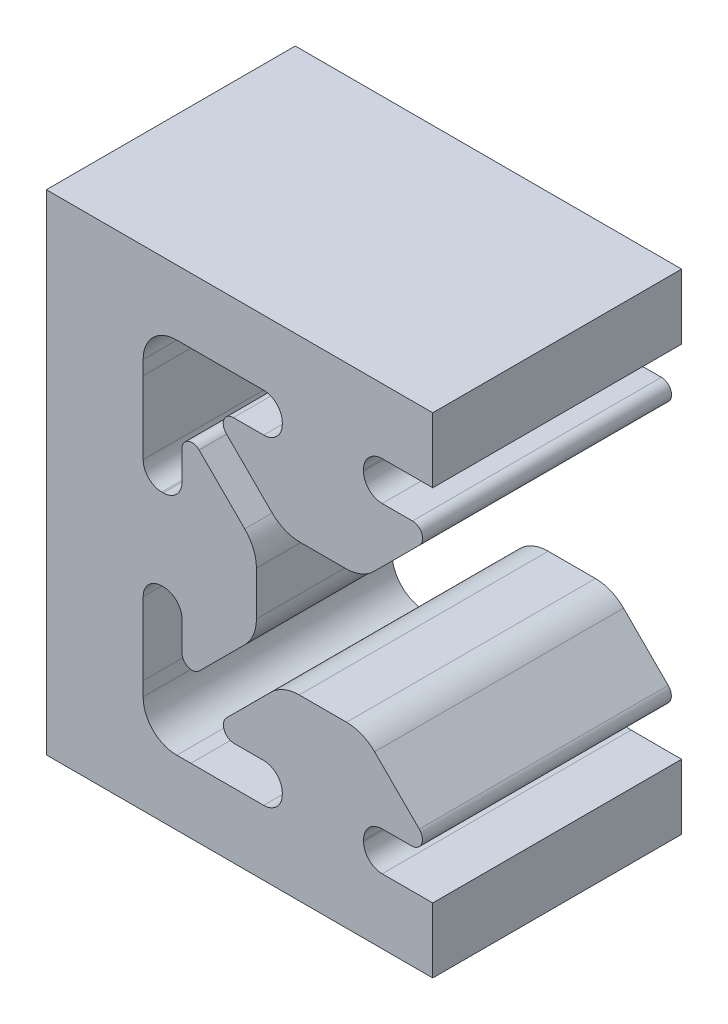
SolidWorks part; units mm, degrees
ref_plane "Front Plane" through (0, 0, 0) normal (0, 0, 1) x (1, 0, 0)
ref_plane "Top Plane" through (0, 0, 0) normal (0, 1, 0) x (1, 0, 0)
ref_plane "Right Plane" through (0, 0, 0) normal (1, 0, 0) x (0, 0, -1)
sketch "Sketch1" plane through (0, 0, 0) normal (0, 0, 1) x (1, 0, 0)
  line L0 (6.3331, -12.7) -> (5.3171, -12.7) construction
  line L1 (-5.3171, -12.7) -> (-6.3331, -12.7) construction
  line L2 (-9.5504, -12.7) -> (-10.5664, -12.6998) construction
  line L3 (-12.6998, -10.5664) -> (-12.7, -9.5504) construction
  line L4 (-12.7, -6.3331) -> (-12.7, -5.3171) construction
  line L5 (-12.7, 5.3171) -> (-12.7, 6.4021) construction
  line L6 (-12.7, 9.5504) -> (-12.6998, 10.5664) construction
  line L7 (-10.5664, 12.6998) -> (-9.5504, 12.7) construction
  line L8 (-6.3331, 12.7) -> (-5.3171, 12.7) construction
  line L9 (5.3171, 12.7) -> (6.3331, 12.7) construction
  line L10 (7.9418, -13) -> (7.9418, -17.7)
  line L12 (7.9418, -17.7) -> (-20, -17.7)
  line L13 (-20, -17.7) -> (-20, 17.6998)
  line L15 (-20, 17.6998) -> (7.9418, 17.6998)
  line L16 (7.9418, 17.6998) -> (7.9418, 13)
  line L17 (7.9418, 13) -> (6.3331, 13)
  line L18 (5.3171, 13) -> (6.3331, 13)
  line L19 (5.3171, 13) -> (4.2875, 13)
  line L20 (2.9385, 11.651) -> (2.9385, 11.5392)
  line L21 (4.2875, 10.1902) -> (6.4768, 10.1902)
  line L22 (6.9951, 8.9367) -> (3.6864, 5.6355)
  line L23 (1.6558, 4.7958) -> (-1.6558, 4.7958)
  line L24 (-3.6864, 5.6355) -> (-6.9951, 8.9367)
  line L25 (-6.4768, 10.1902) -> (-4.2875, 10.1902)
  line L26 (-2.9385, 11.5392) -> (-2.9385, 11.651)
  line L27 (-4.2875, 13) -> (-5.3171, 13)
  line L28 (-6.3331, 13) -> (-5.3171, 13)
  line L29 (-6.3331, 13) -> (-9.5505, 13)
  line L30 (-10.5647, 12.9998) -> (-9.5505, 13)
  line L31 (-13, 9.5504) -> (-12.9998, 10.5647)
  line L32 (-13, 9.5504) -> (-13, 5.3171)
  line L33 (-5.6529, -3.6284) -> (-8.949, -6.917) construction
  line L34 (-13, 5.3171) -> (-13, 4.2875)
  line L35 (-11.651, 2.9385) -> (-11.5392, 2.9385)
  line L36 (-10.1902, 4.2875) -> (-10.1902, 6.4021)
  line L37 (-8.949, 6.917) -> (-5.6529, 3.6284)
  line L38 (-4.8085, 1.5932) -> (-4.8085, -1.5932)
  line L39 (-5.6529, -3.6284) -> (-8.949, -6.917)
  line L40 (-10.1902, -6.4021) -> (-10.1902, -4.2875)
  line L41 (-11.5392, -2.9385) -> (-11.651, -2.9385)
  line L42 (-13, -4.2875) -> (-13, -5.3171)
  line L43 (-13, -6.3331) -> (-13, -5.3171)
  line L44 (-13, -6.3331) -> (-13, -9.5504)
  line L45 (-12.9998, -10.5647) -> (-13, -9.5504)
  line L46 (-9.5505, -13) -> (-10.5647, -12.9998)
  line L47 (-9.5505, -13) -> (-6.3331, -13)
  line L48 (-5.3171, -13) -> (-6.3331, -13)
  line L49 (-5.3171, -13) -> (-4.2875, -13)
  line L50 (-2.9385, -11.651) -> (-2.9385, -11.5392)
  line L51 (-4.2875, -10.1902) -> (-6.4164, -10.1902)
  line L52 (-6.9677, -8.8575) -> (-3.7403, -5.636)
  line L53 (-1.7093, -4.7958) -> (1.7093, -4.7958)
  line L54 (3.7403, -5.636) -> (6.9677, -8.8575)
  line L55 (6.4164, -10.1902) -> (4.2875, -10.1902)
  line L56 (2.9385, -11.5392) -> (2.9385, -11.651)
  line L57 (4.2875, -13) -> (5.3171, -13)
  line L58 (6.3331, -13) -> (5.3171, -13)
  line L59 (6.3331, -13) -> (7.9418, -13)
  line L60 (6.3331, -13) -> (9.5504, -13) construction
  line L61 (7.9418, 13) -> (7.9418, -13) construction
  line L62 (-10.1902, -6.4021) -> (-10.1902, -4.2875) construction
  line L63 (-2.9385, -11.651) -> (-2.9385, -11.5392) construction
  line L64 (9.5504, 13) -> (6.3331, 13) construction
  line L88 (-7.1797, -8.6452) -> (-3.9523, -5.4237) construction
  line L89 (-1.7093, -4.4958) -> (1.7093, -4.4958) construction
  line L90 (3.9523, -5.4237) -> (7.1797, -8.6452) construction
  line L91 (6.4164, -10.4902) -> (4.2875, -10.4902) construction
  line L92 (3.2385, -11.5392) -> (3.2385, -11.651) construction
  line L93 (4.2875, -12.7) -> (5.3171, -12.7) construction
  line L94 (6.3331, -12.7) -> (9.5504, -12.7) construction
  line L95 (12.7, -9.5504) -> (12.7, -6.3331) construction
  line L96 (12.7, -5.3171) -> (12.7, -4.2875) construction
  line L97 (11.651, -3.2385) -> (11.5392, -3.2385) construction
  line L98 (10.4902, -4.2875) -> (10.4902, -6.4021) construction
  line L99 (8.7371, -7.1294) -> (5.441, -3.8408) construction
  line L100 (4.5085, -1.5932) -> (4.5085, 1.5932) construction
  line L101 (5.441, 3.8408) -> (8.7371, 7.1294) construction
  line L102 (10.4902, 6.4021) -> (10.4902, 4.2875) construction
  line L103 (11.5392, 3.2385) -> (11.651, 3.2385) construction
  line L104 (12.7, 4.2875) -> (12.7, 5.3171) construction
  line L105 (12.7, 6.3331) -> (12.7, 9.5504) construction
  line L106 (9.5504, 12.7) -> (6.3331, 12.7) construction
  line L107 (5.3171, 12.7) -> (4.2875, 12.7) construction
  line L108 (3.2385, 11.651) -> (3.2385, 11.5392) construction
  line L109 (4.2875, 10.4902) -> (6.4768, 10.4902) construction
  line L110 (7.207, 8.7244) -> (3.8983, 5.4232) construction
  line L111 (1.6558, 4.4958) -> (-1.6558, 4.4958) construction
  line L112 (-3.8983, 5.4232) -> (-7.207, 8.7244) construction
  line L113 (-6.4768, 10.4902) -> (-4.2875, 10.4902) construction
  line L114 (-3.2385, 11.5392) -> (-3.2385, 11.651) construction
  line L115 (-4.2875, 12.7) -> (-5.3171, 12.7) construction
  line L116 (-6.3331, 12.7) -> (-9.5504, 12.7) construction
  line L117 (-12.7, 9.5504) -> (-12.7, 6.3331) construction
  line L118 (-12.7, 5.3171) -> (-12.7, 4.2875) construction
  line L119 (-11.651, 3.2385) -> (-11.5392, 3.2385) construction
  line L120 (-10.4902, 4.2875) -> (-10.4902, 6.4021) construction
  line L121 (-8.7371, 7.1294) -> (-5.441, 3.8408) construction
  line L122 (-4.5085, 1.5932) -> (-4.5085, -1.5932) construction
  line L123 (-5.441, -3.8408) -> (-8.7371, -7.1294) construction
  line L124 (-10.4902, -6.4021) -> (-10.4902, -4.2875) construction
  line L125 (-11.5392, -3.2385) -> (-11.651, -3.2385) construction
  line L126 (-12.7, -4.2875) -> (-12.7, -5.3171)
  line L127 (-12.7, -6.3331) -> (-12.7, -9.5504) construction
  line L128 (-9.5504, -12.7) -> (-6.3331, -12.7) construction
  line L129 (-5.3171, -12.7) -> (-4.2875, -12.7) construction
  line L130 (-3.2385, -11.651) -> (-3.2385, -11.5392) construction
  line L131 (-4.2875, -10.4902) -> (-6.4164, -10.4902) construction
  line L132 (-13, 9.5504) -> (-13, 6.3331) construction
  line L133 (-13, 5.3171) -> (-13, 6.4021) construction
  arc A0 (4.2875, 13) -> (2.9385, 11.651) centre (4.2875, 11.651) ccw
  arc A2 (2.9385, 11.5392) -> (4.2875, 10.1902) centre (4.2875, 11.5392) ccw
  arc A3 (6.9951, 8.9367) -> (6.4768, 10.1902) centre (6.4768, 9.4563) ccw
  arc A4 (1.6558, 4.7958) -> (3.6864, 5.6355) centre (1.6558, 7.6708) ccw
  arc A5 (-3.6864, 5.6355) -> (-1.6558, 4.7958) centre (-1.6558, 7.6708) ccw
  arc A6 (-6.4768, 10.1902) -> (-6.9951, 8.9367) centre (-6.4768, 9.4563) ccw
  arc A7 (-4.2875, 10.1902) -> (-2.9385, 11.5392) centre (-4.2875, 11.5392) ccw
  arc A8 (-2.9385, 11.651) -> (-4.2875, 13) centre (-4.2875, 11.651) ccw
  arc A9 (-10.5647, 12.9998) -> (-12.9998, 10.5647) centre (-10.5918, 10.5918) ccw
  arc A10 (-13, 4.2875) -> (-11.651, 2.9385) centre (-11.651, 4.2875) ccw
  arc A11 (-11.5392, 2.9385) -> (-10.1902, 4.2875) centre (-11.5392, 4.2875) ccw
  arc A12 (-8.949, 6.917) -> (-10.1902, 6.4021) centre (-9.4628, 6.4021) ccw
  arc A13 (-4.8085, 1.5932) -> (-5.6529, 3.6284) centre (-7.6835, 1.5932) ccw
  arc A14 (-5.6529, -3.6284) -> (-4.8085, -1.5932) centre (-7.6835, -1.5932) ccw
  arc A15 (-10.1902, -6.4021) -> (-8.949, -6.917) centre (-9.4628, -6.4021) ccw
  arc A16 (-10.1902, -4.2875) -> (-11.5392, -2.9385) centre (-11.5392, -4.2875) ccw
  arc A17 (-11.651, -2.9385) -> (-13, -4.2875) centre (-11.651, -4.2875) ccw
  arc A18 (-12.9998, -10.5647) -> (-10.5647, -12.9998) centre (-10.5918, -10.5918) ccw
  arc A19 (-4.2875, -13) -> (-2.9385, -11.651) centre (-4.2875, -11.651) ccw
  arc A20 (-2.9385, -11.5392) -> (-4.2875, -10.1902) centre (-4.2875, -11.5392) ccw
  arc A21 (-6.9677, -8.8575) -> (-6.4164, -10.1902) centre (-6.4164, -9.4098) ccw
  arc A22 (-1.7093, -4.7958) -> (-3.7403, -5.636) centre (-1.7093, -7.6708) ccw
  arc A23 (3.7403, -5.636) -> (1.7093, -4.7958) centre (1.7093, -7.6708) ccw
  arc A24 (6.4164, -10.1902) -> (6.9677, -8.8575) centre (6.4164, -9.4098) ccw
  arc A25 (4.2875, -10.1902) -> (2.9385, -11.5392) centre (4.2875, -11.5392) ccw
  arc A26 (2.9385, -11.651) -> (4.2875, -13) centre (4.2875, -11.651) ccw
  arc A104 (-7.1797, -8.6452) -> (-6.4164, -10.4902) centre (-6.4164, -9.4098) ccw construction
  arc A105 (-1.7093, -4.4958) -> (-3.9523, -5.4237) centre (-1.7093, -7.6708) ccw construction
  arc A106 (3.9523, -5.4237) -> (1.7093, -4.4958) centre (1.7093, -7.6708) ccw construction
  arc A107 (6.4164, -10.4902) -> (7.1797, -8.6452) centre (6.4164, -9.4098) ccw construction
  arc A108 (4.2875, -10.4902) -> (3.2385, -11.5392) centre (4.2875, -11.5392) ccw construction
  arc A109 (3.2385, -11.651) -> (4.2875, -12.7) centre (4.2875, -11.651) ccw construction
  arc A111 (10.5664, -12.6998) -> (9.5504, -12.7) centre (10.0584, -12.7) ccw construction
  arc A112 (10.5664, -12.6998) -> (12.6998, -10.5664) centre (10.5918, -10.5918) ccw construction
  arc A113 (12.7, -9.5504) -> (12.6998, -10.5664) centre (12.7, -10.0584) ccw construction
  arc A114 (12.7, -5.3171) -> (12.7, -6.3331) centre (12.7, -5.8251) ccw construction
  arc A115 (12.7, -4.2875) -> (11.651, -3.2385) centre (11.651, -4.2875) ccw construction
  arc A116 (11.5392, -3.2385) -> (10.4902, -4.2875) centre (11.5392, -4.2875) ccw construction
  arc A117 (8.7371, -7.1294) -> (10.4902, -6.4021) centre (9.4628, -6.4021) ccw construction
  arc A118 (4.5085, -1.5932) -> (5.441, -3.8408) centre (7.6835, -1.5932) ccw construction
  arc A119 (5.441, 3.8408) -> (4.5085, 1.5932) centre (7.6835, 1.5932) ccw construction
  arc A120 (10.4902, 6.4021) -> (8.7371, 7.1294) centre (9.4628, 6.4021) ccw construction
  arc A121 (10.4902, 4.2875) -> (11.5392, 3.2385) centre (11.5392, 4.2875) ccw construction
  arc A122 (11.651, 3.2385) -> (12.7, 4.2875) centre (11.651, 4.2875) ccw construction
  arc A123 (12.7, 6.3331) -> (12.7, 5.3171) centre (12.7, 5.8251) ccw construction
  arc A124 (12.6998, 10.5664) -> (12.7, 9.5504) centre (12.7, 10.0584) ccw construction
  arc A125 (12.6998, 10.5664) -> (10.5664, 12.6998) centre (10.5918, 10.5918) ccw construction
  arc A126 (9.5504, 12.7) -> (10.5664, 12.6998) centre (10.0584, 12.7) ccw construction
  arc A128 (4.2875, 12.7) -> (3.2385, 11.651) centre (4.2875, 11.651) ccw construction
  arc A129 (3.2385, 11.5392) -> (4.2875, 10.4902) centre (4.2875, 11.5392) ccw construction
  arc A130 (7.207, 8.7244) -> (6.4768, 10.4902) centre (6.4768, 9.4563) ccw construction
  arc A131 (1.6558, 4.4958) -> (3.8983, 5.4232) centre (1.6558, 7.6708) ccw construction
  arc A132 (-3.8983, 5.4232) -> (-1.6558, 4.4958) centre (-1.6558, 7.6708) ccw construction
  arc A133 (-6.4768, 10.4902) -> (-7.207, 8.7244) centre (-6.4768, 9.4563) ccw construction
  arc A134 (-4.2875, 10.4902) -> (-3.2385, 11.5392) centre (-4.2875, 11.5392) ccw construction
  arc A135 (-3.2385, 11.651) -> (-4.2875, 12.7) centre (-4.2875, 11.651) ccw construction
  arc A138 (-10.5664, 12.6998) -> (-12.6998, 10.5664) centre (-10.5918, 10.5918) ccw construction
  arc A141 (-12.7, 4.2875) -> (-11.651, 3.2385) centre (-11.651, 4.2875) ccw construction
  arc A142 (-11.5392, 3.2385) -> (-10.4902, 4.2875) centre (-11.5392, 4.2875) ccw construction
  arc A143 (-8.7371, 7.1294) -> (-10.4902, 6.4021) centre (-9.4628, 6.4021) ccw construction
  arc A144 (-4.5085, 1.5932) -> (-5.441, 3.8408) centre (-7.6835, 1.5932) ccw construction
  arc A145 (-5.441, -3.8408) -> (-4.5085, -1.5932) centre (-7.6835, -1.5932) ccw construction
  arc A146 (-10.4902, -6.4021) -> (-8.7371, -7.1294) centre (-9.4628, -6.4021) ccw construction
  arc A147 (-10.4902, -4.2875) -> (-11.5392, -3.2385) centre (-11.5392, -4.2875) ccw construction
  arc A148 (-11.651, -3.2385) -> (-12.7, -4.2875) centre (-11.651, -4.2875) ccw construction
  arc A151 (-12.6998, -10.5664) -> (-10.5664, -12.6998) centre (-10.5918, -10.5918) ccw construction
  arc A154 (-4.2875, -12.7) -> (-3.2385, -11.651) centre (-4.2875, -11.651) ccw construction
  arc A155 (-3.2385, -11.5392) -> (-4.2875, -10.4902) centre (-4.2875, -11.5392) ccw construction
  point P0 (-13, 7.4338)
  dimension "D5" = 7
  dimension "D6" = 20.9418
  dimension "D1" = 0.3
  dimension "D2" = 0.3
  dimension "D3" = 0.3
  dimension "D4" = 0.3
extrude "Boss-Extrude1" add sketch "Sketch1" along normal blind 18
sketch "Sketch2" plane through (-20, 0, 0) normal (-1, 0, 0) x (0, 0, 1)
  line L2 (18, -17.7) -> (0, -17.7) construction
  line L5 (18, -17.7) -> (18, 17.6998) construction
  circle A0 centre (5.25, -0.7) radius 1.75
  circle A1 centre (12.75, -0.7) radius 1.75
  circle A2 centre (5.25, -6.7) radius 1.75
  circle A3 centre (12.75, -6.7) radius 1.75
  dimension "D1" = 3.5
  dimension "D2" = 3.5
  dimension "D3" = 17
  dimension "D4" = 17
  dimension "D5" = 7.5
  dimension "D6" = 5.25
extrude "Cut-Extrude1" cut sketch "Sketch2" against normal blind 7
